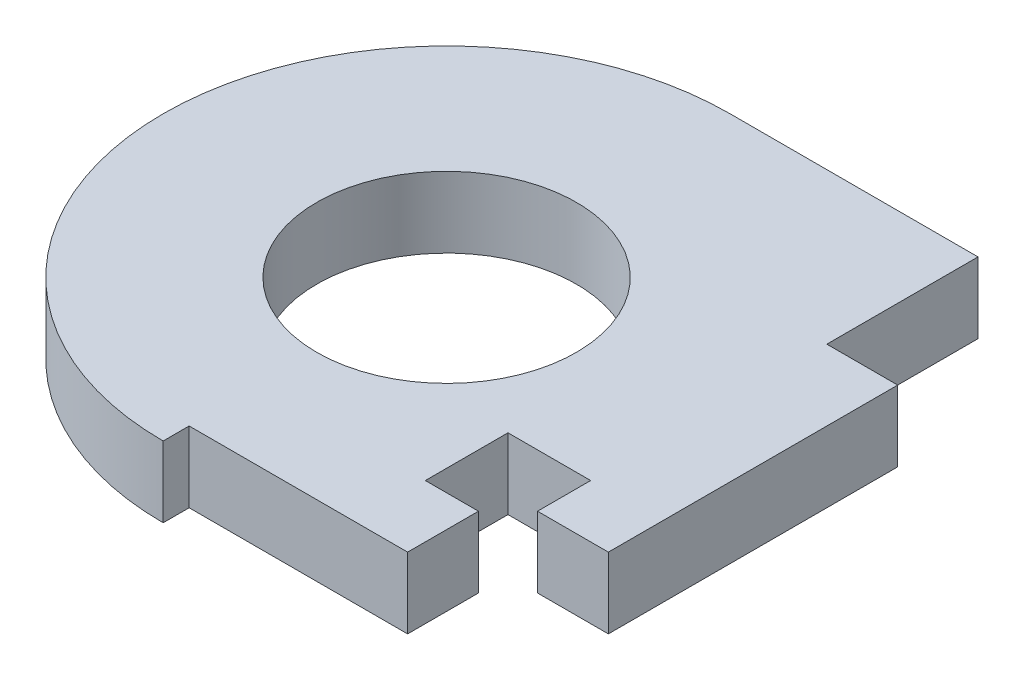
SolidWorks part; units mm, degrees
ref_plane "Front Plane" through (0, 0, 0) normal (0, 0, 1) x (1, 0, 0)
ref_plane "Top Plane" through (0, 0, 0) normal (0, 1, 0) x (1, 0, 0)
ref_plane "Right Plane" through (0, 0, 0) normal (1, 0, 0) x (0, 0, -1)
sketch "Sketch1" plane through (0, 0, 0) normal (0, 1, 0) x (1, 0, 0)
  line L0 (0, 0) -> (0, 7)
  line L5 (-14, -8.2) -> (-14, -6)
  line L7 (-14, -6) -> (4.5, -6)
  line L9 (0, 0) -> (4.5, 0)
  line L12 (4.5, 0) -> (4.5, -6)
  line L13 (0, 7) -> (7, 7)
  line L17 (7, 39.8) -> (7, 27)
  line L28 (7, 27) -> (13, 27)
  line L31 (7, 7) -> (7, 2.5)
  line L32 (7, 2.5) -> (13, 2.5)
  line L34 (13, 2.5) -> (13, 27)
  line L35 (-14, 39.8) -> (7, 39.8)
  arc A0 (-14, 39.8) -> (-14, -8.2) centre (-14, 15.8) ccw
  circle A1 centre (-14, 15.8) radius 11
  dimension "D3" = 24
  dimension "D4" = 22
  dimension "D10" = 6
  dimension "D1" = 15.8
  dimension "D2" = 21
  dimension "D5" = 6
  dimension "D6" = 18.5
  dimension "D7" = 7
  dimension "D8" = 7
  dimension "D9" = 4.5
  dimension "D11" = 4.5
  dimension "D12" = 20
extrude "Boss-Extrude1" add sketch "Sketch1" along normal blind 6
